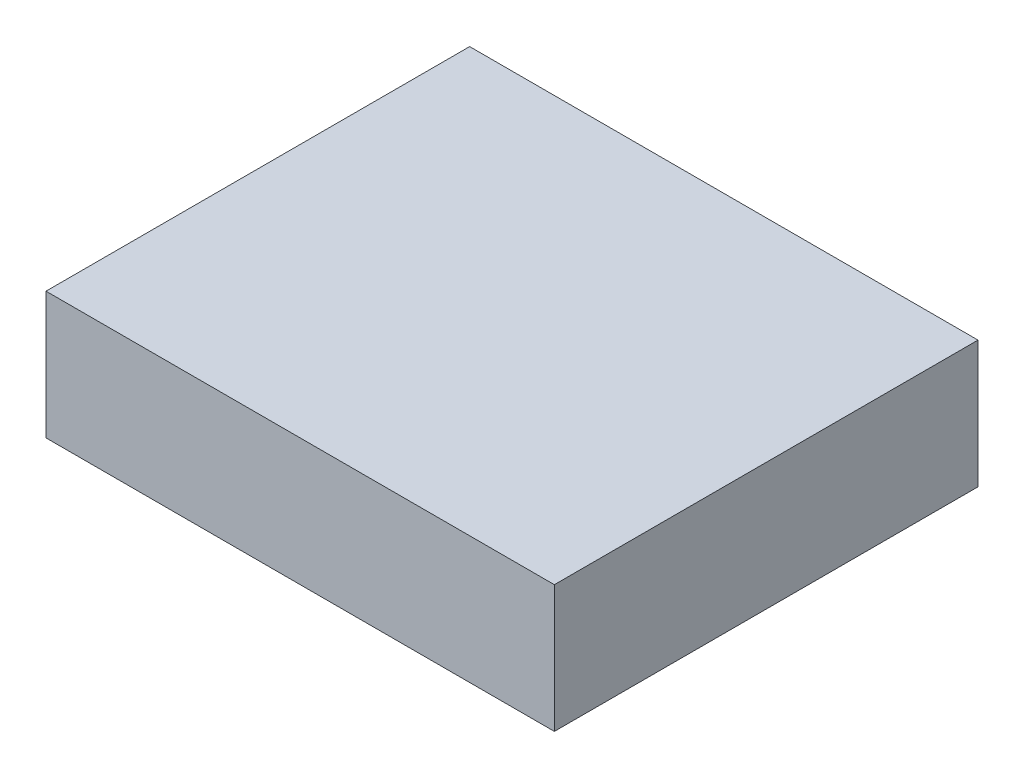
SolidWorks part; units mm, degrees
ref_plane "Front Plane" through (0, 0, 0) normal (0, 0, 1) x (1, 0, 0)
ref_plane "Top Plane" through (0, 0, 0) normal (0, 1, 0) x (1, 0, 0)
ref_plane "Right Plane" through (0, 0, 0) normal (1, 0, 0) x (0, 0, -1)
sketch "Sketch1" plane through (0, 0, 0) normal (0, 1, 0) x (1, 0, 0)
  line L1 (0, 0) -> (60, 0)
  line L2 (0, 0) -> (0, 50)
  line L3 (0, 50) -> (60, 50)
  line L4 (60, 0) -> (60, 50)
  dimension "D1" = 50
  dimension "D2" = 60
extrude "Boss-Extrude1" add sketch "Sketch1" along normal blind 15
